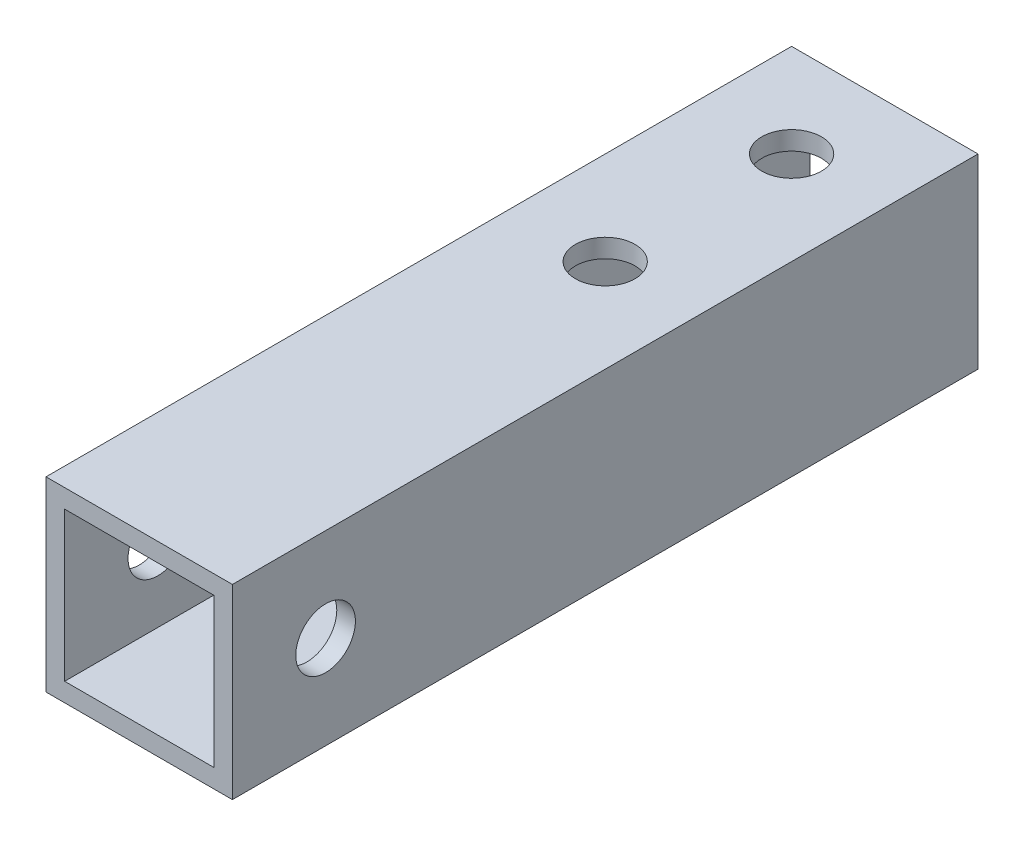
SolidWorks part; units mm, degrees
material "6061 合金"
ref_plane "正面" through (0, 0, 0) normal (0, 0, 1) x (1, 0, 0)
ref_plane "平面" through (0, 0, 0) normal (0, 1, 0) x (1, 0, 0)
ref_plane "右側面" through (0, 0, 0) normal (1, 0, 0) x (0, 0, -1)
sketch "断面 スケッチ" plane through (0, 0, 0) normal (0, 0, 1) x (1, 0, 0)
  line L1 (-5, -5) -> (5, -5)
  line L2 (-5, -5) -> (-5, 5)
  line L3 (-5, 5) -> (5, 5)
  line L4 (5, -5) -> (5, 5)
  line L5 (-5, -5) -> (5, 5) construction
  line L6 (-5, 5) -> (5, -5) construction
  point P0 (0, 0)
  dimension "D1" = 10
extrude "フレーム全長" add sketch "断面 スケッチ" along normal blind 40 thin thin type one direction reverse wall 1
sketch "上面穴 スケッチ" plane through (0, 5, 0) normal (0, 1, 0) x (1, 0, 0)
  line L0 (0, 0) -> (0, -40) construction
  line L1 (5, 0) -> (-5, 0) construction
  line L2 (5, -40) -> (-5, -40) construction
  line L3 (-5, -20) -> (5, -20) construction
  line L4 (-5, -40) -> (-5, 0) construction
  line L5 (5, -40) -> (5, 0) construction
  circle A0 centre (0, -5) radius 1.6
  circle A1 centre (0, -15) radius 1.6
  dimension "D1" = 5
  dimension "D2" = 3.2
  dimension "D3" = 10
sketch "側面穴 スケッチ" plane through (5, 0, 0) normal (1, 0, 0) x (0, 0, -1)
  line L0 (0, 0) -> (-40, 0) construction
  line L1 (0, -5) -> (0, 5) construction
  line L2 (-40, -5) -> (-40, 5) construction
  line L3 (-20, 5) -> (-20, -5) construction
  line L4 (-40, 5) -> (0, 5) construction
  line L5 (-40, -5) -> (0, -5) construction
  circle A0 centre (-35, 0) radius 1.6
  dimension "D1" = 35
  dimension "D2" = 3.2
extrude "上面穴貫通" cut sketch "上面穴 スケッチ" against normal through all
extrude "側面穴貫通" cut sketch "側面穴 スケッチ" against normal through all
fillet "フィレット" [suppressed] radius 5
